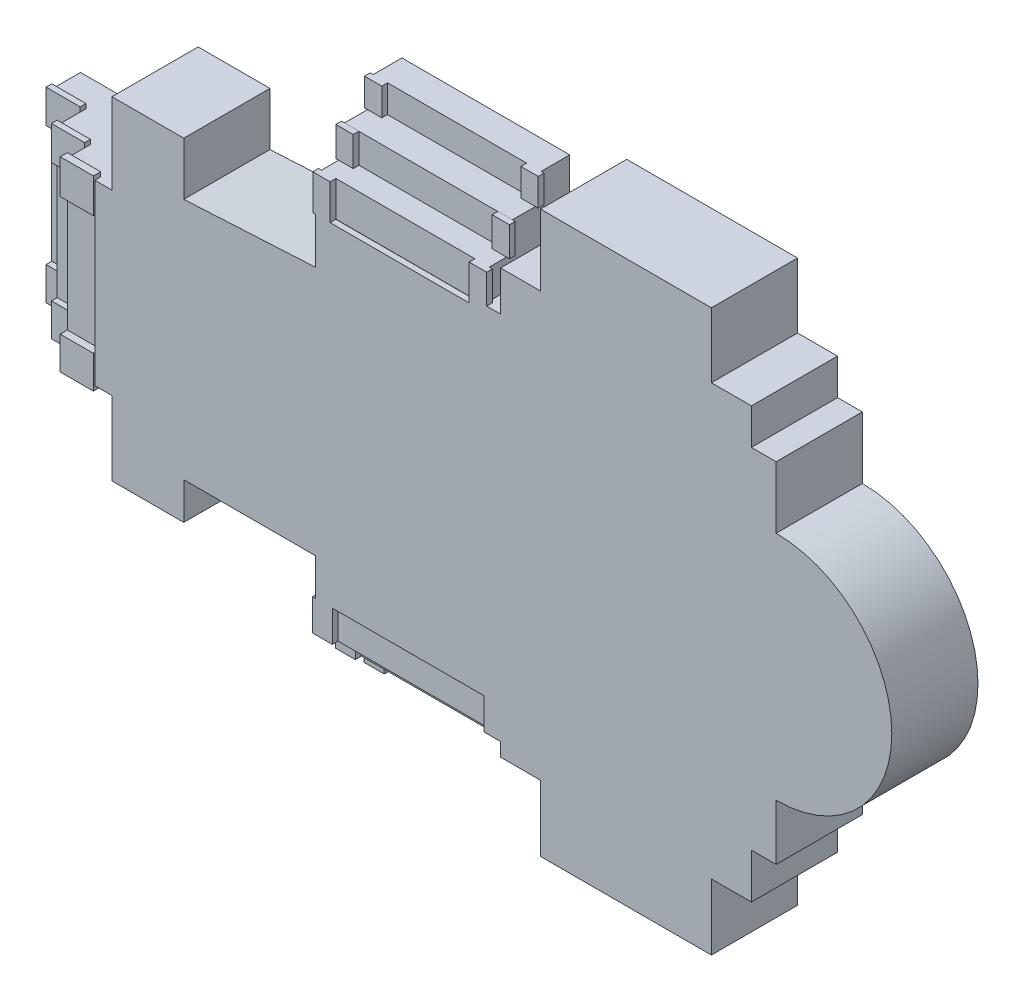
SolidWorks part; units mm, degrees
ref_plane "Front Plane" through (0, 0, 0) normal (0, 0, 1) x (1, 0, 0)
ref_plane "Top Plane" through (0, 0, 0) normal (0, 1, 0) x (1, 0, 0)
ref_plane "Right Plane" through (0, 0, 0) normal (1, 0, 0) x (0, 0, -1)
sketch "Sketch1" plane through (0, 0, 0) normal (0, 0, 1) x (1, 0, 0)
  line L0 (-801.717, 253.5304) -> (-417.717, 253.5304) construction
  line L1 (-237.1288, 421.0918) -> (-237.1288, 454.1321)
  line L2 (-237.1288, 482.9989) -> (-206.1753, 482.9989)
  line L3 (-206.1753, 482.9989) -> (-206.1753, 492.7371)
  line L4 (-206.1753, 492.7371) -> (-160.2667, 495.1717)
  line L5 (-160.2667, 495.1717) -> (-160.2667, 511.1701)
  line L6 (-160.2667, 511.1701) -> (-131.0521, 511.1701)
  line L7 (-131.0521, 511.1701) -> (-131.0521, 531.6899)
  line L8 (-131.0521, 531.6899) -> (-101.8375, 531.6899)
  line L9 (-101.8375, 531.6899) -> (-101.8375, 513.2569)
  line L10 (-101.8375, 513.2569) -> (-95.9251, 513.2569)
  line L11 (-95.9251, 513.2569) -> (-95.9251, 527.1686)
  line L12 (-95.9251, 527.1686) -> (-82.0134, 527.1686)
  line L13 (-82.0134, 527.1686) -> (-82.0134, 551.8618)
  line L14 (-82.0134, 551.8618) -> (-22.5408, 551.8618)
  line L15 (-22.5408, 551.8618) -> (-22.5408, 529.2553)
  line L16 (-22.5408, 529.2553) -> (-8.6291, 529.2553)
  line L17 (-8.6291, 529.2553) -> (-8.6291, 516.7348)
  line L18 (-8.6291, 516.7348) -> (0, 516.7348)
  line L19 (0, 516.7348) -> (0, 495.1717)
  line L20 (-237.1288, 482.9989) -> (-237.1288, 454.1321)
  line L21 (-237.1288, 421.0918) -> (-206.1753, 421.0918)
  line L22 (-206.1753, 421.0918) -> (-206.1753, 408.2235)
  line L23 (-206.1753, 408.2235) -> (-160.2667, 408.2235)
  line L24 (-160.2667, 408.2235) -> (-160.2667, 395.3552)
  line L25 (-160.2667, 395.3552) -> (-131.0521, 395.3552)
  line L26 (-131.0521, 395.3552) -> (-131.0521, 374.8354)
  line L29 (-101.8375, 395.3552) -> (-95.9251, 395.3552)
  line L30 (-95.9251, 395.3552) -> (-95.9251, 379.7045)
  line L31 (-95.9251, 379.7045) -> (-82.0134, 379.7045)
  line L32 (-82.0134, 379.7045) -> (-82.0134, 356.7502)
  line L33 (-82.0134, 356.7502) -> (-22.5408, 356.7502)
  line L34 (-22.5408, 356.7502) -> (-22.5408, 379.7045)
  line L35 (-22.5408, 379.7045) -> (-8.6291, 379.7045)
  line L36 (-8.6291, 379.7045) -> (-8.6291, 395.3552)
  line L37 (-8.6291, 395.3552) -> (0, 395.3552)
  line L38 (0, 395.3552) -> (0, 414.6577)
  line L39 (-131.0521, 374.8354) -> (-101.8375, 374.8354)
  line L40 (-131.0521, 511.1701) -> (-101.8375, 511.1701)
  line L41 (-131.0521, 511.1701) -> (-131.0521, 531.6899)
  line L42 (-131.0521, 531.6899) -> (-101.8375, 531.6899)
  line L43 (-101.8375, 511.1701) -> (-101.8375, 531.6899)
  line L44 (-101.8375, 531.6899) -> (-131.0521, 531.6899)
  line L45 (-101.8375, 531.6899) -> (-101.8375, 511.1701)
  line L46 (-101.8375, 511.1701) -> (-131.0521, 511.1701)
  line L47 (-131.0521, 531.6899) -> (-131.0521, 511.1701)
  line L48 (-131.0521, 395.3552) -> (-101.8375, 395.3552)
  line L52 (-101.8375, 395.3552) -> (-101.8375, 374.8354)
  line L58 (-237.1288, 464.5659) -> (-255.9096, 464.5659)
  line L59 (-237.1288, 464.5659) -> (-237.1288, 435.3513)
  line L60 (-237.1288, 435.3513) -> (-255.9096, 435.3513)
  line L61 (-255.9096, 464.5659) -> (-255.9096, 435.3513)
  arc A0 (0, 495.1717) -> (0, 414.6577) centre (0, 454.9147) cw
extrude "Boss-Extrude1" add sketch "Sketch1" along normal blind 30 contours A0 L19 L18 L17 L16 L15 L14 L13 L12 L11 L10 L43 L40 L6 L5 L4 L3 L2 L20 L1 L21 L22 L23 L24 L25 L48 L29 L30 L31 L32 L33 L34 L35 L36 L37 L38
sketch "Sketch4" plane through (0, 0, 0) normal (0, 0, -1) x (-1, 0, 0)
  line L1 (237.1288, 421.0918) -> (272.1288, 421.0918)
  line L2 (237.1288, 421.0918) -> (237.1288, 482.9989)
  line L3 (237.1288, 482.9989) -> (272.1288, 482.9989)
  line L4 (272.1288, 421.0918) -> (272.1288, 482.9989)
  dimension "D1" = 35
extrude "Boss-Extrude2" add sketch "Sketch4" against normal blind 10
sketch "Sketch5" plane through (0, 0, 10) normal (0, 0, 1) x (1, 0, 0)
  line L0 (-237.1288, 421.0918) -> (-272.1288, 421.0918) construction
  line L13 (-237.1288, 482.9989) -> (-260.2329, 482.9989)
  line L14 (-237.1288, 482.9989) -> (-237.1288, 421.0918)
  line L15 (-237.1288, 421.0918) -> (-260.2329, 421.0918)
  line L16 (-260.2329, 482.9989) -> (-260.2329, 421.0918)
extrude "Boss-Extrude3" add sketch "Sketch5" along normal blind 10
sketch "Sketch6" plane through (0, 0, 20) normal (0, 0, 1) x (1, 0, 0)
  line L0 (-260.2329, 421.0918) -> (-237.1288, 421.0918) construction
  line L5 (-237.1288, 482.9989) -> (-248.6809, 482.9989)
  line L6 (-237.1288, 482.9989) -> (-237.1288, 421.0918)
  line L7 (-237.1288, 421.0918) -> (-248.6809, 421.0918)
  line L8 (-248.6809, 482.9989) -> (-248.6809, 421.0918)
extrude "Boss-Extrude5" add sketch "Sketch6" along normal blind 8
sketch "Sketch8" plane through (0, 0, 10) normal (0, 0, 1) x (1, 0, 0)
  line L0 (-272.1288, 421.0918) -> (-272.1288, 482.9989) construction
  line L5 (-260.2329, 482.9989) -> (-260.2329, 421.0918) construction
  line L11 (-272.1288, 419.601) -> (-260.2329, 419.601)
  line L12 (-272.1288, 419.601) -> (-272.1288, 431.0918)
  line L13 (-272.1288, 431.0918) -> (-260.2329, 431.0918)
  line L14 (-260.2329, 419.601) -> (-260.2329, 431.0918)
  line L15 (-272.1288, 484.5686) -> (-260.2329, 484.5686)
  line L16 (-272.1288, 484.5686) -> (-272.1288, 472.9989)
  line L17 (-272.1288, 472.9989) -> (-260.2329, 472.9989)
  line L18 (-260.2329, 484.5686) -> (-260.2329, 472.9989)
  point P17 (0, 0)
  point P19 (-272.1288, 484.5686)
extrude "Boss-Extrude6" add sketch "Sketch8" along normal blind 2
sketch "Sketch9" plane through (0, 0, 20) normal (0, 0, 1) x (1, 0, 0)
  line L0 (-248.6809, 482.9989) -> (-248.6809, 421.0918) construction
  line L1 (-260.2329, 484.5686) -> (-248.6809, 484.5686)
  line L2 (-260.2329, 484.5686) -> (-260.2329, 472.8055)
  line L3 (-260.2329, 472.8055) -> (-248.6809, 472.8055)
  line L4 (-248.6809, 484.5686) -> (-248.6809, 472.8055)
  line L5 (-260.2329, 482.9989) -> (-260.2329, 421.0918) construction
  line L6 (-260.2329, 431.0918) -> (-248.6809, 431.0918)
  line L7 (-260.2329, 431.0918) -> (-260.2329, 419.6472)
  line L8 (-260.2329, 419.6472) -> (-248.6809, 419.6472)
  line L9 (-248.6809, 431.0918) -> (-248.6809, 419.6472)
  line L10 (-260.2329, 421.0918) -> (-260.2329, 431.0918) construction
extrude "Boss-Extrude7" add sketch "Sketch9" along normal blind 2
sketch "Sketch10" plane through (0, 0, 28) normal (0, 0, 1) x (1, 0, 0)
  line L0 (-237.1288, 482.9989) -> (-237.1288, 421.0918) construction
  line L5 (-248.6809, 484.5686) -> (-237.1288, 484.5686)
  line L6 (-248.6809, 484.5686) -> (-248.6809, 472.5525)
  line L7 (-248.6809, 472.5525) -> (-237.1288, 472.5525)
  line L8 (-237.1288, 484.5686) -> (-237.1288, 472.5525)
  line L14 (-248.6809, 431.0918) -> (-237.1288, 431.0918)
  line L15 (-248.6809, 431.0918) -> (-248.6809, 419.6788)
  line L16 (-248.6809, 419.6788) -> (-237.1288, 419.6788)
  line L17 (-237.1288, 431.0918) -> (-237.1288, 419.6788)
extrude "Boss-Extrude8" add sketch "Sketch10" along normal blind 2.5
sketch "Sketch11" plane through (0, 0, 0) normal (0, 0, -1) x (-1, 0, 0)
  line L1 (95.9251, 395.3552) -> (160.2667, 395.3552)
  line L2 (95.9251, 395.3552) -> (95.9251, 366.5381)
  line L3 (95.9251, 366.5381) -> (160.2667, 366.5381)
  line L4 (160.2667, 395.3552) -> (160.2667, 366.5381)
extrude "Boss-Extrude9" add sketch "Sketch11" against normal blind 10
sketch "Sketch12" plane through (0, 0, 10) normal (0, 0, 1) x (1, 0, 0)
  line L0 (-95.9251, 379.7045) -> (-95.9251, 366.5381) construction
  line L1 (-160.2667, 395.3552) -> (-95.9251, 395.3552)
  line L2 (-160.2667, 395.3552) -> (-160.2667, 375.9421)
  line L3 (-160.2667, 375.9421) -> (-95.9251, 375.9421)
  line L4 (-95.9251, 395.3552) -> (-95.9251, 375.9421)
extrude "Boss-Extrude10" add sketch "Sketch12" along normal blind 10
sketch "Sketch13" plane through (0, 0, 20) normal (0, 0, 1) x (1, 0, 0)
  line L0 (-95.9251, 379.7045) -> (-95.9251, 395.3552) construction
  line L1 (-160.2667, 395.3552) -> (-95.9251, 395.3552)
  line L2 (-160.2667, 395.3552) -> (-160.2667, 384.4191)
  line L3 (-160.2667, 384.4191) -> (-95.9251, 384.4191)
  line L4 (-95.9251, 395.3552) -> (-95.9251, 384.4191)
extrude "Boss-Extrude11" add sketch "Sketch13" along normal blind 8
sketch "Sketch14" plane through (0, 0, 10) normal (0, 0, 1) x (1, 0, 0)
  line L0 (-95.9251, 366.5381) -> (-160.2667, 366.5381) construction
  line L1 (-161.4099, 375.8404) -> (-154.4099, 375.8404)
  line L2 (-161.4099, 375.8404) -> (-161.4099, 366.5381)
  line L3 (-161.4099, 366.5381) -> (-154.4099, 366.5381)
  line L4 (-154.4099, 375.8404) -> (-154.4099, 366.5381)
  line L6 (-94.695, 375.8404) -> (-101.695, 375.8404)
  line L7 (-94.695, 375.8404) -> (-94.695, 366.5381)
  line L8 (-94.695, 366.5381) -> (-101.695, 366.5381)
  line L9 (-101.695, 375.8404) -> (-101.695, 366.5381)
  dimension "D1" = 7
  dimension "D2" = 7
extrude "Boss-Extrude12" add sketch "Sketch14" along normal blind 2
sketch "Sketch15" plane through (0, 0, 20) normal (0, 0, 1) x (1, 0, 0)
  line L0 (-160.2667, 384.4191) -> (-95.9251, 384.4191) construction
  line L1 (-161.4099, 375.8404) -> (-154.4551, 375.8404)
  line L2 (-161.4099, 375.8404) -> (-161.4099, 384.4191)
  line L3 (-161.4099, 384.4191) -> (-154.4551, 384.4191)
  line L4 (-154.4551, 375.8404) -> (-154.4551, 384.4191)
  line L5 (-160.2667, 384.4191) -> (-95.9251, 384.4191) construction
  line L6 (-94.695, 375.8404) -> (-101.6224, 375.8404)
  line L7 (-94.695, 375.8404) -> (-94.695, 384.4191)
  line L8 (-94.695, 384.4191) -> (-101.6224, 384.4191)
  line L9 (-101.6224, 375.8404) -> (-101.6224, 384.4191)
extrude "Boss-Extrude13" add sketch "Sketch15" along normal blind 2
sketch "Sketch16" plane through (0, 0, 28) normal (0, 0, 1) x (1, 0, 0)
  line L0 (-95.9251, 395.3552) -> (-160.2667, 395.3552) construction
  line L9 (-161.4099, 384.4191) -> (-154.4835, 384.4191)
  line L10 (-161.4099, 384.4191) -> (-161.4099, 395.3552)
  line L11 (-161.4099, 395.3552) -> (-154.4835, 395.3552)
  line L12 (-154.4835, 384.4191) -> (-154.4835, 395.3552)
  line L14 (-101.6224, 384.4191) -> (-94.8935, 384.4191)
  line L15 (-101.6224, 384.4191) -> (-101.6224, 395.3552)
  line L16 (-101.6224, 395.3552) -> (-94.8935, 395.3552)
  line L17 (-94.8935, 384.4191) -> (-94.8935, 395.3552)
extrude "Boss-Extrude14" add sketch "Sketch16" along normal blind 2
sketch "Sketch17" plane through (0, 0, 0) normal (0, 0, -1) x (-1, 0, 0)
  line L9 (101.8375, 511.1701) -> (160.2548, 511.1701)
  line L10 (101.8375, 511.1701) -> (101.8375, 543.3084)
  line L11 (101.8375, 543.3084) -> (160.2548, 543.3084)
  line L12 (160.2548, 511.1701) -> (160.2548, 543.3084)
extrude "Boss-Extrude15" add sketch "Sketch17" against normal blind 10
sketch "Sketch18" plane through (0, 0, 10) normal (0, 0, 1) x (1, 0, 0)
  line L0 (-101.8375, 543.3084) -> (-101.8375, 513.2569) construction
  line L1 (-160.2667, 511.1701) -> (-101.8375, 511.1701)
  line L2 (-160.2667, 511.1701) -> (-160.2667, 533.7118)
  line L3 (-160.2667, 533.7118) -> (-101.8375, 533.7118)
  line L4 (-101.8375, 511.1701) -> (-101.8375, 533.7118)
extrude "Boss-Extrude16" add sketch "Sketch18" along normal blind 10
sketch "Sketch19" plane through (0, 0, 20) normal (0, 0, 1) x (1, 0, 0)
  line L0 (-101.8375, 513.2569) -> (-101.8375, 533.7118) construction
  line L9 (-160.2667, 511.1701) -> (-101.8375, 511.1701)
  line L10 (-160.2667, 511.1701) -> (-160.2667, 523.4844)
  line L11 (-160.2667, 523.4844) -> (-101.8375, 523.4844)
  line L12 (-101.8375, 511.1701) -> (-101.8375, 523.4844)
extrude "Boss-Extrude17" add sketch "Sketch19" along normal blind 8
sketch "Sketch20" plane through (-206.1753, 0, 0) normal (-1, 0, 0) x (0, 0, 1)
  line L5 (0, 511.1701) -> (30, 511.1701)
  line L6 (0, 511.1701) -> (0, 395.3552)
  line L7 (0, 395.3552) -> (30, 395.3552)
  line L8 (30, 511.1701) -> (30, 395.3552)
extrude "Boss-Extrude18" add sketch "Sketch20" along normal blind 25
sketch "Sketch21" plane through (0, 0, 10) normal (0, 0, 1) x (1, 0, 0)
  line L0 (-160.2548, 543.3084) -> (-101.8375, 543.3084) construction
  line L1 (-161.2623, 533.7647) -> (-155.2469, 533.7647)
  line L2 (-161.2623, 533.7647) -> (-161.2623, 543.3084)
  line L3 (-161.2623, 543.3084) -> (-155.2469, 543.3084)
  line L4 (-155.2469, 533.7647) -> (-155.2469, 543.3084)
  line L6 (-100.8271, 533.7647) -> (-106.8425, 533.7647)
  line L7 (-100.8271, 533.7647) -> (-100.8271, 543.3084)
  line L8 (-100.8271, 543.3084) -> (-106.8425, 543.3084)
  line L9 (-106.8425, 533.7647) -> (-106.8425, 543.3084)
extrude "Boss-Extrude19" add sketch "Sketch21" along normal blind 2
sketch "Sketch22" plane through (0, 0, 20) normal (0, 0, 1) x (1, 0, 0)
  line L0 (-101.8375, 523.4844) -> (-160.2667, 523.4844) construction
  line L5 (-161.2623, 533.7647) -> (-155.2035, 533.7647)
  line L6 (-161.2623, 533.7647) -> (-161.2623, 523.4844)
  line L7 (-161.2623, 523.4844) -> (-155.2035, 523.4844)
  line L8 (-155.2035, 533.7647) -> (-155.2035, 523.4844)
  line L10 (-106.8425, 533.7647) -> (-100.8143, 533.7647)
  line L11 (-106.8425, 533.7647) -> (-106.8425, 523.4844)
  line L12 (-106.8425, 523.4844) -> (-100.8143, 523.4844)
  line L13 (-100.8143, 533.7647) -> (-100.8143, 523.4844)
extrude "Boss-Extrude20" add sketch "Sketch22" along normal blind 2
sketch "Sketch23" plane through (0, 0, 28) normal (0, 0, 1) x (1, 0, 0)
  line L0 (-160.2667, 511.1701) -> (-101.8375, 511.1701) construction
  line L1 (-161.2623, 523.4844) -> (-155.2598, 523.4844)
  line L2 (-161.2623, 523.4844) -> (-161.2623, 511.1701)
  line L3 (-161.2623, 511.1701) -> (-155.2598, 511.1701)
  line L4 (-155.2598, 523.4844) -> (-155.2598, 511.1701)
  line L5 (-101.8375, 523.4844) -> (-160.2667, 523.4844) construction
  line L6 (-106.8425, 523.4844) -> (-100.737, 523.4844)
  line L7 (-106.8425, 523.4844) -> (-106.8425, 511.1701)
  line L8 (-106.8425, 511.1701) -> (-100.737, 511.1701)
  line L9 (-100.737, 523.4844) -> (-100.737, 511.1701)
  line L10 (-106.8425, 523.4844) -> (-101.8375, 523.4844) construction
extrude "Boss-Extrude21" add sketch "Sketch23" along normal blind 2
sketch "Sketch24" plane through (0, 0, 0) normal (0, 0, -1) x (-1, 0, 0)
  line L2 (228.9799, 479.7598) -> (228.9799, 506.732)
  line L3 (228.9799, 506.732) -> (209.5, 506.732)
  line L4 (209.5, 506.732) -> (209.5, 490.249)
  line L5 (209.5, 490.249) -> (156.4546, 490.249)
  line L9 (107.0055, 511.2274) -> (92.92, 511.2274)
  line L10 (92.92, 511.2274) -> (92.92, 524.8634)
  line L11 (92.92, 524.8634) -> (77.9354, 524.8634)
  line L12 (77.9354, 524.8634) -> (77.9354, 546.8907)
  line L13 (77.9354, 546.8907) -> (26.0888, 546.8907)
  line L14 (26.0888, 546.8907) -> (26.0888, 527.7104)
  line L15 (26.0888, 527.7104) -> (13.202, 527.7104)
  line L16 (13.202, 527.7104) -> (13.202, 514.3742)
  line L17 (13.202, 514.3742) -> (4.511, 514.3742)
  line L18 (4.511, 514.3742) -> (4.511, 493.2459)
  line L20 (228.9799, 399.4425) -> (209.5, 399.4425)
  line L21 (209.5, 399.4425) -> (209.5, 410.531)
  line L22 (209.5, 410.531) -> (156.4546, 410.531)
  line L27 (80.6326, 381.1613) -> (80.6326, 358.6844)
  line L28 (80.6326, 358.6844) -> (26.0888, 358.6844)
  line L29 (26.0888, 358.6844) -> (26.0888, 381.1613)
  line L30 (26.0888, 381.1613) -> (10.8045, 381.1613)
  line L31 (10.8045, 381.1613) -> (10.8045, 396.7452)
  line L32 (10.8045, 396.7452) -> (2.1135, 396.7452)
  line L33 (2.1135, 396.7452) -> (2.1135, 417.1243)
  line L34 (228.9799, 424.0172) -> (228.9799, 399.4425)
  line L35 (107.0055, 511.2274) -> (156.4546, 511.2274)
  line L37 (228.9799, 479.7598) -> (228.9799, 424.0172)
  line L39 (156.4546, 511.2274) -> (156.4546, 490.249)
  line L40 (80.6326, 381.1613) -> (80.6326, 390.7514)
  line L43 (80.6326, 390.7514) -> (80.6326, 399.4425)
  line L44 (80.6326, 399.4425) -> (156.4546, 399.4425)
  line L45 (156.4546, 410.531) -> (156.4546, 399.4425)
  arc A0 (4.511, 493.2459) -> (2.1135, 417.1243) centre (3.3122, 455.1851) ccw
extrude "Cut-Extrude2" cut sketch "Sketch24" against normal blind 28
